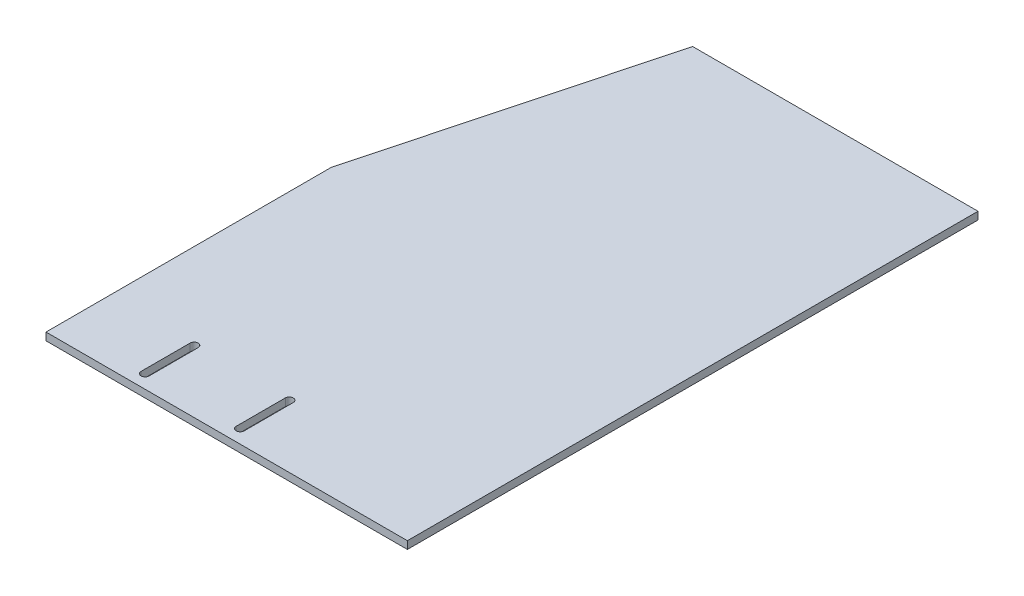
SolidWorks part; units mm, degrees
ref_plane "Front Plane" through (0, 0, 0) normal (1, 0, 0) x (0, 1, 0)
ref_plane "Top Plane" through (0, 0, 0) normal (0, 0, 1) x (0, 1, 0)
ref_plane "Right Plane" through (0, 0, 0) normal (0, 1, 0) x (-1, 0, 0)
sketch "Sketch1" plane through (0, 0, 0) normal (0, 1, 0) x (-1, 0, 0)
  line L0 (0, 0) -> (0, 150)
  line L1 (0, 150) -> (-190, 150)
  line L2 (-190, 150) -> (-190, -150)
  line L3 (-190, -150) -> (-40, -150)
  line L4 (-40, -150) -> (0, 0)
  line L5 (-95, 142.9) -> (-95, 117.1) construction
  line L6 (-97.1, 142.9) -> (-97.1, 117.1)
  line L7 (-92.9, 142.9) -> (-92.9, 117.1)
  line L8 (-70, 150) -> (-70, 107.928) construction
  line L9 (-45, 142.9) -> (-45, 117.1) construction
  line L10 (-42.9, 142.9) -> (-42.9, 117.1)
  line L11 (-47.1, 142.9) -> (-47.1, 117.1)
  arc A0 (-97.1, 142.9) -> (-92.9, 142.9) centre (-95, 142.9) cw
  arc A1 (-92.9, 117.1) -> (-97.1, 117.1) centre (-95, 117.1) cw
  arc A2 (-42.9, 142.9) -> (-47.1, 142.9) centre (-45, 142.9) ccw
  arc A3 (-47.1, 117.1) -> (-42.9, 117.1) centre (-45, 117.1) ccw
  point P8 (-95, 130)
  point P17 (-45, 130)
  dimension "D5" = 30
  dimension "D7" = 5
  dimension "D1" = 150
  dimension "D2" = 190
  dimension "D3" = 150
  dimension "D4" = 300
  dimension "D6" = 4.2
  dimension "D8" = 50
  dimension "D9" = 70
extrude "Boss-Extrude1" add sketch "Sketch1" along normal blind 4
